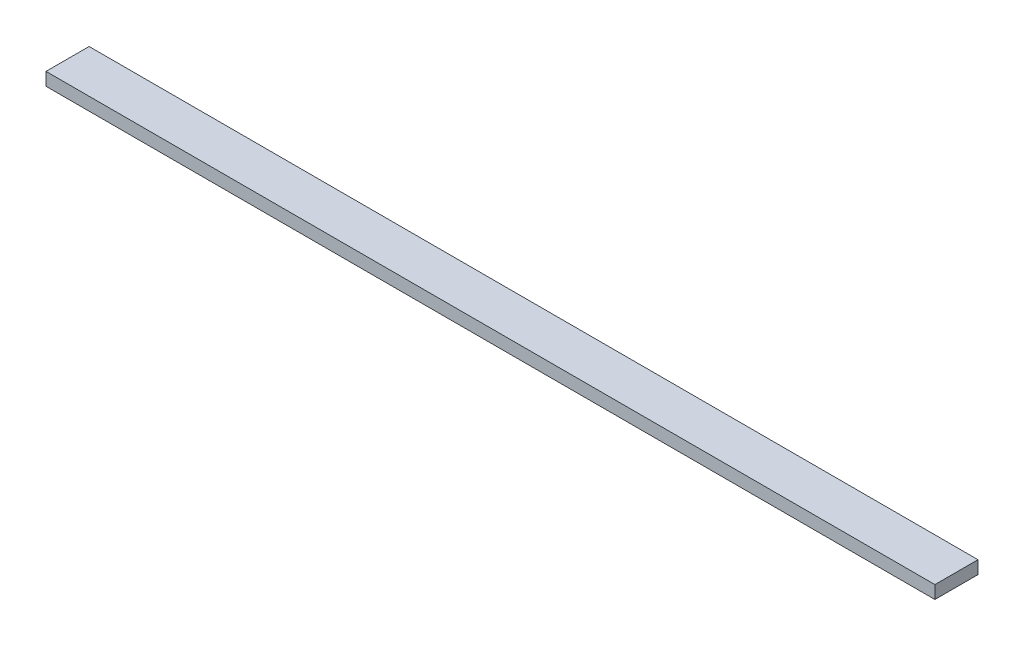
SolidWorks part; units mm, degrees
ref_plane "Front Plane" through (0, 0, 0) normal (0, 0, 1) x (1, 0, 0)
ref_plane "Top Plane" through (0, 0, 0) normal (0, 1, 0) x (1, 0, 0)
ref_plane "Right Plane" through (0, 0, 0) normal (1, 0, 0) x (0, 0, -1)
sketch "Sketch1" plane through (0, 0, 0) normal (0, 1, 0) x (1, 0, 0)
  line L6 (103.12, 0) -> (-103.12, 0)
  line L8 (-103.12, 0) -> (-103.12, 10)
  line L9 (-103.12, 10) -> (103.12, 10)
  line L10 (103.12, 10) -> (103.12, 0)
  dimension "D1" = 10
  dimension "D2" = 206.24
extrude "Boss-Extrude1" add sketch "Sketch1" along normal blind 3
